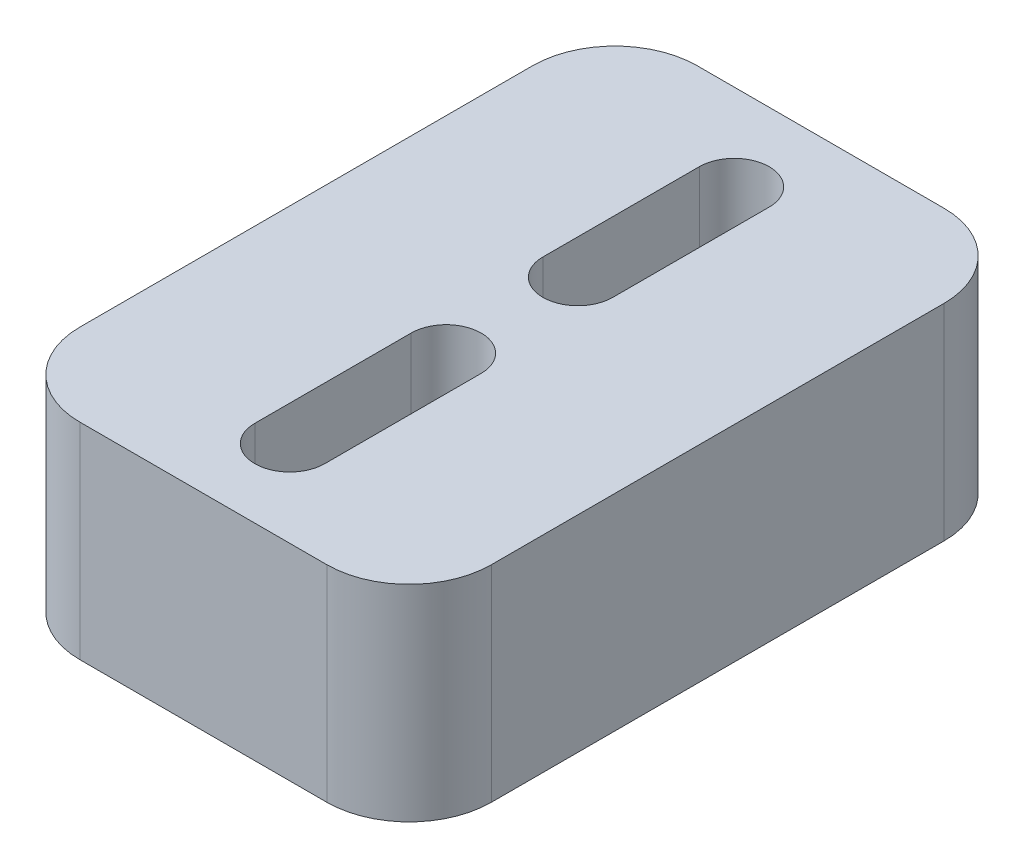
SolidWorks part; units mm, degrees
material "Custom PLA"
ref_plane "Front Plane" through (0, 0, 0) normal (0, 0, 1) x (1, 0, 0)
ref_plane "Top Plane" through (0, 0, 0) normal (0, 1, 0) x (1, 0, 0)
ref_plane "Right Plane" through (0, 0, 0) normal (1, 0, 0) x (0, 0, -1)
sketch "Sketch1" plane through (0, 0, 0) normal (0, 1, 0) x (1, 0, 0)
  line L0 (0, 10.8) -> (0, 3.2) construction
  line L1 (-10, -15) -> (10, -15)
  line L2 (-10, -15) -> (-10, 15)
  line L3 (-10, 15) -> (10, 15)
  line L4 (10, -15) -> (10, 15)
  line L5 (0, 15) -> (0, -15) construction
  line L6 (-10, 0) -> (10, 0) construction
  line L7 (1.7, 10.8) -> (1.7, 3.2)
  line L8 (-1.7, 10.8) -> (-1.7, 3.2)
  line L9 (0, -10.8) -> (0, -3.2) construction
  line L10 (1.7, -10.8) -> (1.7, -3.2)
  line L11 (-1.7, -10.8) -> (-1.7, -3.2)
  circle A4 centre (0, 5) radius 1.7 construction
  arc A6 (1.7, 10.8) -> (-1.7, 10.8) centre (0, 10.8) ccw
  arc A7 (-1.7, 3.2) -> (1.7, 3.2) centre (0, 3.2) ccw
  arc A8 (1.7, -10.8) -> (-1.7, -10.8) centre (0, -10.8) cw
  arc A9 (-1.7, -3.2) -> (1.7, -3.2) centre (0, -3.2) cw
  point P0 (0, 0)
  point P6 (0, 1.5)
  point P10 (0, 7)
  point P16 (0, -7)
  point P22 (0, 12.5)
  dimension "D1" = 1.5
  dimension "D2" = 5
  dimension "D5" = 3.4
  dimension "D3" = 20
  dimension "D4" = 30
  dimension "D6" = 2.5
extrude "Boss-Extrude1" add sketch "Sketch1" along normal blind 10
fillet "Fillet1" radius 4 4 edges at (-10, 5, 15) (-10, 5, -15) (10, 5, -15) (10, 5, 15)
